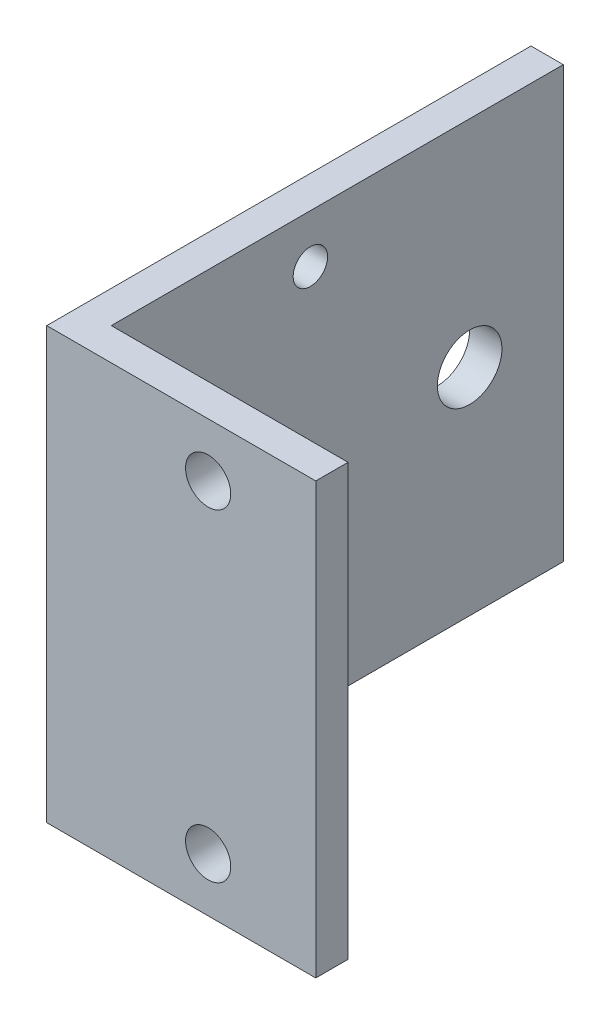
SolidWorks part; units mm, degrees
ref_plane "前视基准面" through (0, 0, 0) normal (0, 0, 1) x (1, 0, 0)
ref_plane "上视基准面" through (0, 0, 0) normal (0, 1, 0) x (1, 0, 0)
ref_plane "右视基准面" through (0, 0, 0) normal (1, 0, 0) x (0, 0, -1)
ref_plane "基准面4" through (-63, 0, 0) normal (-1, 0, 0) x (0, -1, 0)
sketch "草图1" plane through (-63, 0, 0) normal (-1, 0, 0) x (0, -1, 0)
  line L0 (-220, -5) -> (-220, -50)
  line L1 (-220, -50) -> (-180, -50)
  line L2 (-180, -50) -> (-180, -5)
  line L3 (-180, -5) -> (-220, -5)
  dimension "D1" = 40
  dimension "D2" = 45
extrude "凸台-拉伸1" add sketch "草图1" against normal blind 25
sketch "草图2" plane through (0, 220, 0) normal (0, 1, 0) x (-1, 0, 0)
  line L0 (38, -58) -> (60, -58)
  line L1 (60, -58) -> (60, -8)
  line L2 (60, -8) -> (38, -8)
  line L3 (38, -8) -> (38, -58)
  dimension "D1" = 50
extrude "切除-拉伸1" cut sketch "草图2" against normal through all
sketch "草图3" plane through (-63, 0, 0) normal (-1, 0, 0) x (0, 0, 1)
  line L0 (-5, 180) -> (-5, 220) construction
  line L2 (-5, 220) -> (-50, 220) construction
  circle A0 centre (-41.3, 200) radius 3
  point P4 (-5, 200)
  dimension "D1" = 36.3
  dimension "D2" = 20
extrude "切除-拉伸2" cut sketch "草图3" against normal through all
hole_wizard "Ø4.2 (4.2) 直径孔1" positions "草图5" profile "草图4" hole size "Ø4.2" standard "ANSI Metric"
sketch "草图5" plane through (0, 0, -8) normal (0, 0, -1) x (-1, 0, 0)
  point P0 (48, 215)
  point P1 (48, 185)
sketch "草图4" plane through (-48, 215, -8) normal (1, 0, 0) x (0, 1, 0)
  line L0 (0, 0) -> (0, 3)
  line L1 (0, 3) -> (2.1, 3)
  line L2 (2.1, 3) -> (2.1, 0)
  line L5 (2.1, 0) -> (0, 0)
  line L11 (0, -6.35) -> (0, 107.95) construction
  dimension "通孔孔直径" = 4.2
  dimension "通孔孔深度" = 3
hole_wizard "Ø3.2 (3.2) 直径孔1" positions "草图7" profile "草图6" hole size "Ø3.2" standard "ANSI Metric"
sketch "草图7" plane through (-63, 0, 0) normal (-1, 0, 0) x (0, 0, 1)
  point P0 (-26.5, 215.5)
  point P1 (-26.5, 184.5)
  point P2 (-13.0766, 207.75)
  point P3 (-13.0766, 192.25)
sketch "草图6" plane through (-63, 215.5, -26.5) normal (0, 1, 0) x (0, 0, 1)
  line L0 (0, 0) -> (0, 25)
  line L1 (0, 25) -> (1.6, 25)
  line L2 (1.6, 25) -> (1.6, 0)
  line L5 (1.6, 0) -> (0, 0)
  line L11 (0, -6.35) -> (0, 107.95) construction
  dimension "通孔孔直径" = 3.2
  dimension "通孔孔深度" = 25
